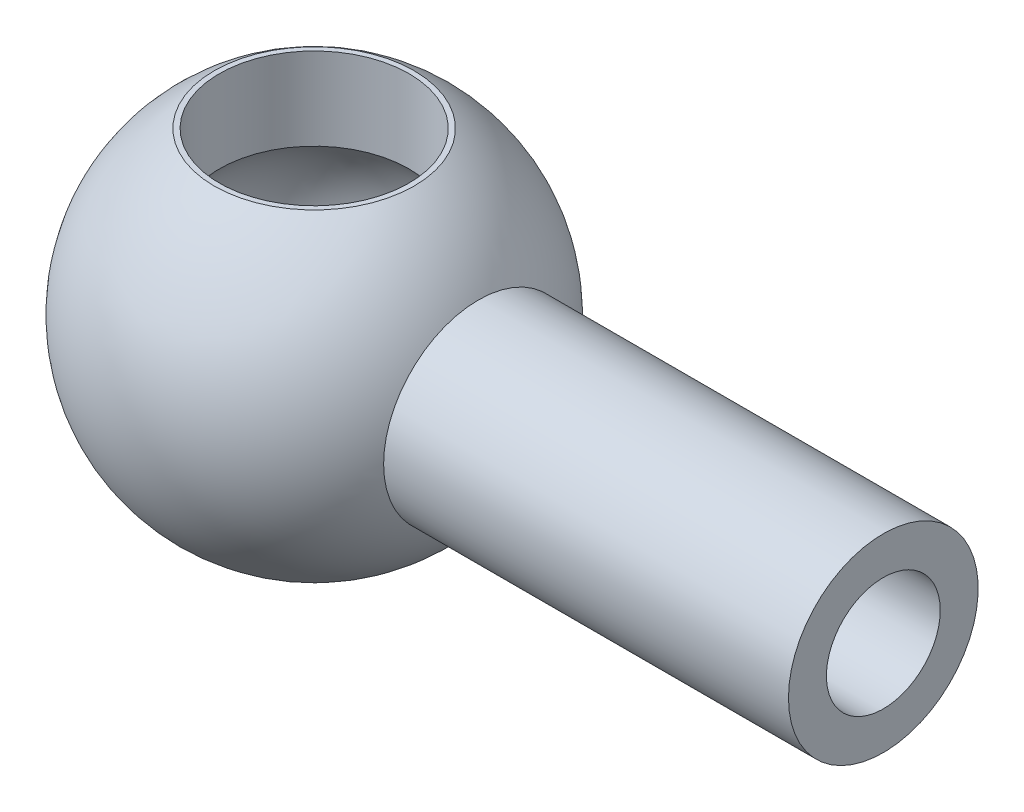
SolidWorks part; units mm, degrees
ref_plane "Ön Düzlem" through (0, 0, 0) normal (0, 0, 1) x (1, 0, 0)
ref_plane "Üst Düzlem" through (0, 0, 0) normal (0, 1, 0) x (1, 0, 0)
ref_plane "Sağ Düzlem" through (0, 0, 0) normal (1, 0, 0) x (0, 0, -1)
sketch "Sketch1" plane through (0, 0, 0) normal (0, 0, 1) x (1, 0, 0)
  line L0 (-13.1157, 0) -> (50.2489, 0) construction
  line L1 (30, -5) -> (30, 0)
  line L2 (-10, 0) -> (-5, 0)
  line L3 (30, -5) -> (8.6603, -5)
  line L4 (5, 0) -> (30, 0)
  arc A0 (-5, 0) -> (5, 0) centre (0, 0) ccw
  arc A1 (-10, 0) -> (8.6603, -5) centre (0, 0) ccw
  point P9 (30, 0)
  dimension "D1" = 10
  dimension "D3" = 20
  dimension "D2" = 5
  dimension "D4" = 30
revolve "Revolve3" add sketch "Sketch1" angle 360 about L0
sketch "Sketch2" plane through (0, 0, 0) normal (0, 0, 1) x (1, 0, 0)
  line L0 (-6.5, 0) -> (6.5, 0) construction
  line L1 (-6.5, 0) -> (6.5, 0)
  arc A1 (-6.5, 0) -> (6.5, 0) centre (0, 0) ccw
  dimension "D1" = 13
sketch "Sketch3" plane through (30, 0, 0) normal (1, 0, 0) x (0, 0, -1)
  circle A0 centre (0, 0) radius 3
  dimension "D1" = 6
extrude "Cut-Extrude2" cut sketch "Sketch3" against normal blind 10
revolve "Cut-Revolve1" cut sketch "Sketch2" angle 360 about L0
sketch "Sketch4" plane through (0, 0, 0) normal (0, 1, 0) x (1, 0, 0)
  circle A0 centre (0, 0) radius 5
  dimension "D1" = 10
extrude "Cut-Extrude3" cut sketch "Sketch4" against normal mid plane 30
sketch "Sketch5" plane through (0, 0, 0) normal (1, 0, 0) x (0, 0, -1)
  line L1 (-12.5, -8.5) -> (12.5, -8.5)
  line L2 (-12.5, -8.5) -> (-12.5, 8.5)
  line L3 (-12.5, 8.5) -> (12.5, 8.5)
  line L4 (12.5, -8.5) -> (12.5, 8.5)
  line L5 (-12.5, -8.5) -> (12.5, 8.5) construction
  line L6 (-12.5, 8.5) -> (12.5, -8.5) construction
  point P0 (0, 0)
  dimension "D1" = 17
extrude "Cut-Extrude-Thin2" cut sketch "Sketch5" against normal blind 10 and the other way blind 10 thin
